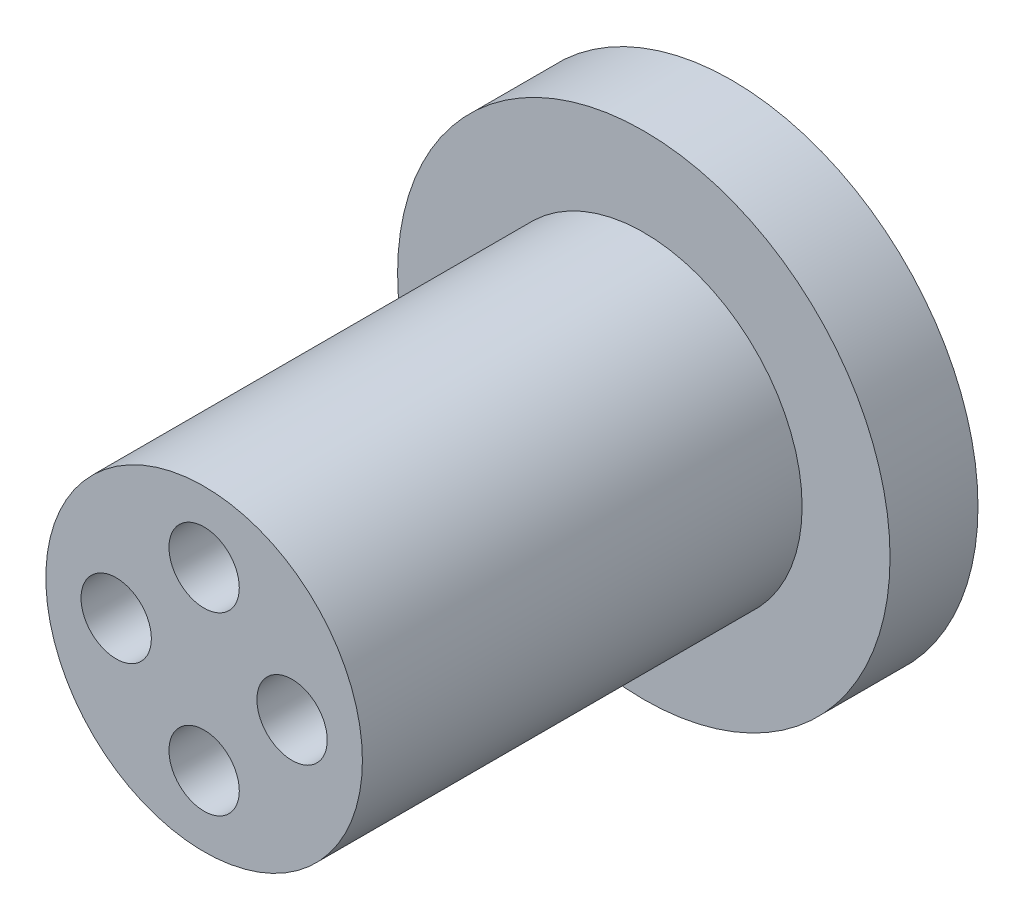
SolidWorks part; units mm, degrees
ref_plane "前视基准面" through (0, 0, 0) normal (0, 0, 1) x (1, 0, 0)
ref_plane "上视基准面" through (0, 0, 0) normal (0, 1, 0) x (1, 0, 0)
ref_plane "右视基准面" through (0, 0, 0) normal (1, 0, 0) x (0, 0, -1)
other "Configuration Table"
sketch "Sketch1" plane through (0, 0, 0) normal (0, 0, 1) x (1, 0, 0)
  circle A0 centre (0, 0) radius 7
  dimension "14" = 14
extrude "Boss-Extrude1" add sketch "Sketch1" along normal blind 2.5
sketch "Sketch2" plane through (0, 0, 2.5) normal (0, 0, 1) x (1, 0, 0)
  circle A0 centre (0, 0) radius 4.5
  dimension "D1" = 9
extrude "Boss-Extrude2" add sketch "Sketch2" along normal blind 12.5
sketch "Sketch3" plane through (0, 0, 15) normal (0, 0, 1) x (1, 0, 0)
  circle A0 centre (0, 0) radius 2.5 construction
  circle A1 centre (0, 2.5) radius 1
  circle A2 centre (2.5, 0) radius 1
  circle A3 centre (0, -2.5) radius 1
  circle A4 centre (-2.5, 0) radius 1
  point P14 (0, 0)
  dimension "D1" = 5
  dimension "D2" = 2
extrude "Cut-Extrude1" cut sketch "Sketch3" against normal blind 5
